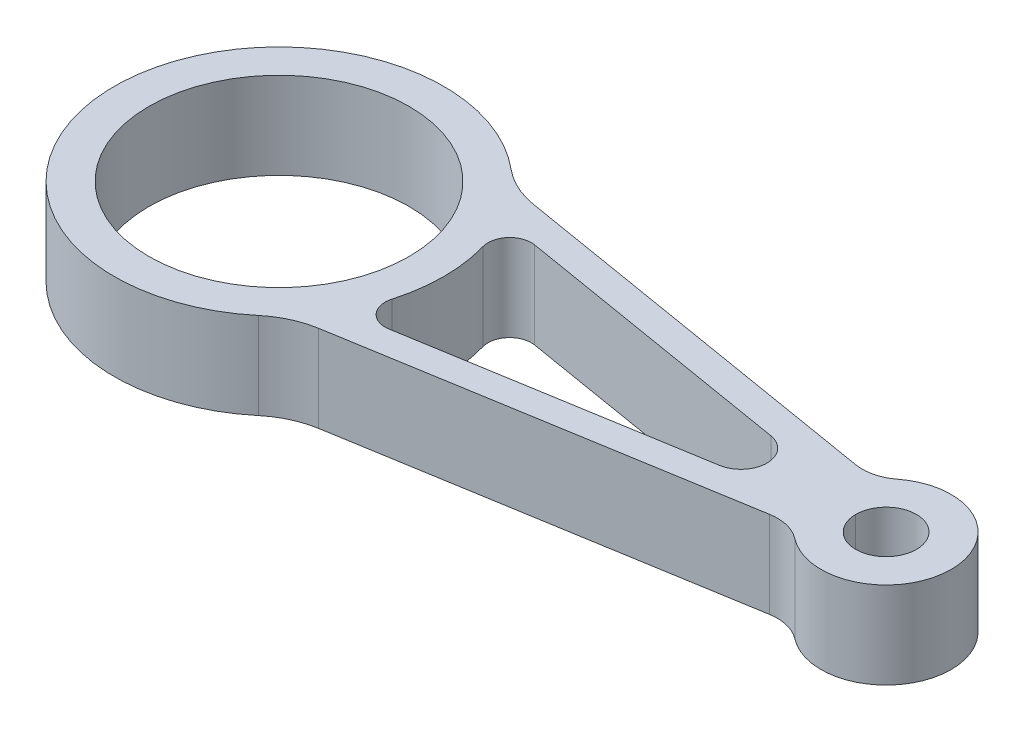
SolidWorks part; units mm, degrees
material "Plain Carbon Steel"
ref_plane "Front Plane" through (0, 0, 0) normal (0, 0, 1) x (1, 0, 0)
ref_plane "Top Plane" through (0, 0, 0) normal (0, 1, 0) x (1, 0, 0)
ref_plane "Right Plane" through (0, 0, 0) normal (1, 0, 0) x (0, 0, -1)
sketch "Sketch1" plane through (0, 0, 0) normal (0, 1, 0) x (1, 0, 0)
  line L0 (0, 0) -> (30, 0) construction
  line L1 (128.0638, 9.0844) -> (27.9355, 25.7606)
  line L2 (128.0638, -9.0844) -> (27.9355, -25.7606)
  line L3 (133, 0) -> (140, 0) construction
  circle A0 centre (0, 0) radius 30
  arc A1 (27.9355, 25.7606) -> (27.9355, -25.7606) centre (0, 0) ccw
  circle A2 centre (140, 0) radius 7
  arc A3 (128.0638, -9.0844) -> (128.0638, 9.0844) centre (140, 0) ccw
  dimension "D2" = 14
  dimension "D3" = 30
  dimension "D4" = 60
  dimension "D5" = 76
  dimension "D1" = 140
extrude "Boss-Extrude1" add sketch "Sketch1" along normal mid plane 20
fillet "Fillet1" radius 10 2 edges at (128.0638, 0, -9.0844) (128.0638, 0, 9.0844)
fillet "Fillet2" radius 20 2 edges at (27.9355, 0, -25.7606) (27.9355, 0, 25.7606)
sketch "Sketch2" plane through (0, 10, 0) normal (0, 1, 0) x (1, 0, 0)
  line L0 (0, 0) -> (176.1437, 0) construction
  line L1 (42.1502, 16.8036) -> (107.5075, 5.9185)
  line L2 (107.5075, -5.9185) -> (42.1502, -16.8036)
  line L3 (123.0688, 9.9163) -> (33.9231, 24.7634) construction
  arc A0 (36.5231, -10.4912) -> (36.5231, 10.4912) centre (0, 0) ccw
  arc A2 (107.5075, 5.9185) -> (107.5075, -5.9185) centre (106.5217, 0) cw
  arc A3 (42.1502, -16.8036) -> (36.5231, -10.4912) centre (41.3288, -11.8716) cw
  arc A4 (42.1502, 16.8036) -> (36.5231, 10.4912) centre (41.3288, 11.8716) ccw
  point P6 (34.3893, 19.0556)
  point P10 (32.6433, 19.453)
  point P13 (32.6777, -19.395)
  point P17 (0, 0)
  dimension "D1" = 76
  dimension "D2" = 6
  dimension "D4" = 5
  dimension "D3" = 6.5
extrude "Cut-Extrude1" cut sketch "Sketch2" against normal blind 65 contours A0 A3 L2 A2 L1 A4
split line "Split Line10"
